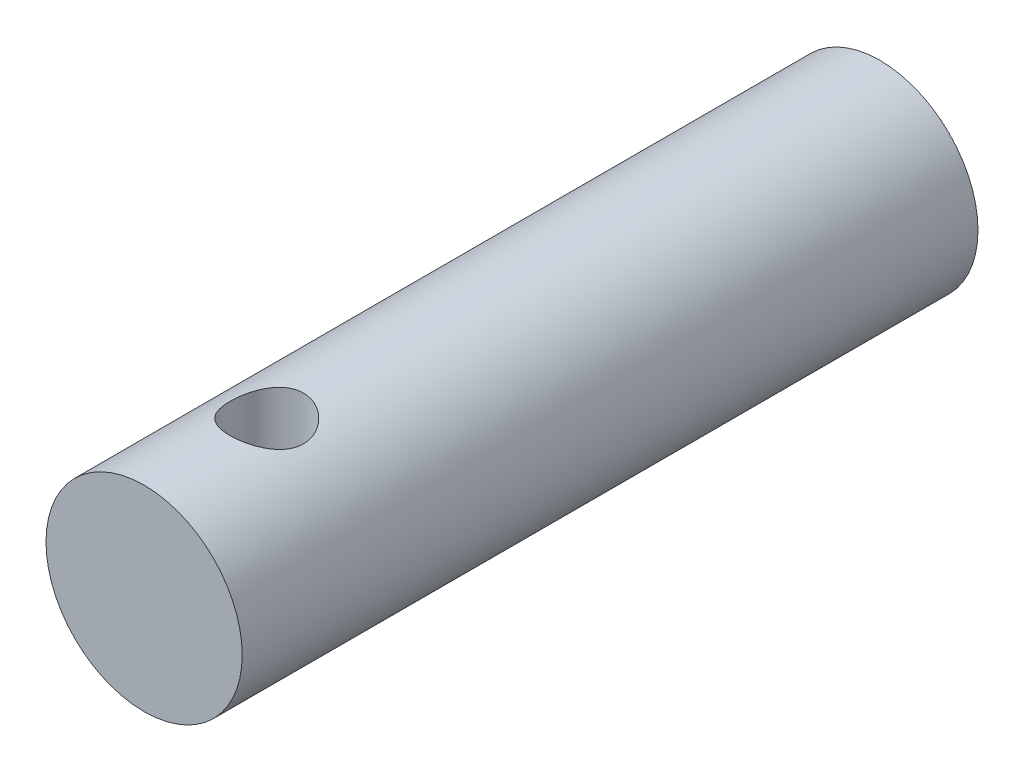
SolidWorks part; units mm, degrees
ref_plane "Alzado" through (0, 0, 0) normal (0, 0, 1) x (1, 0, 0)
ref_plane "Planta" through (0, 0, 0) normal (0, 1, 0) x (1, 0, 0)
ref_plane "Vista lateral" through (0, 0, 0) normal (1, 0, 0) x (0, 0, -1)
sketch "Croquis1" plane through (0, 0, 0) normal (0, 0, 1) x (1, 0, 0)
  circle A0 centre (0, 0) radius 4
  dimension "D1" = 8
extrude "Saliente-Extruir1" add sketch "Croquis1" along normal blind 30
ref_plane "Plano1" through (0, 4, 0) normal (0, 1, 0) x (1, 0, 0)
sketch "Croquis2" plane through (0, 4, 0) normal (0, 1, 0) x (1, 0, 0)
  line L0 (-4, -30) -> (4, -30) construction
  line L1 (-4, 0) -> (-4, -30) construction
  circle A0 centre (0, -25) radius 1.5
  dimension "D1" = 3
  dimension "D2" = 5
  dimension "D3" = 4
extrude "Cortar-Extruir1" cut sketch "Croquis2" against normal through all
